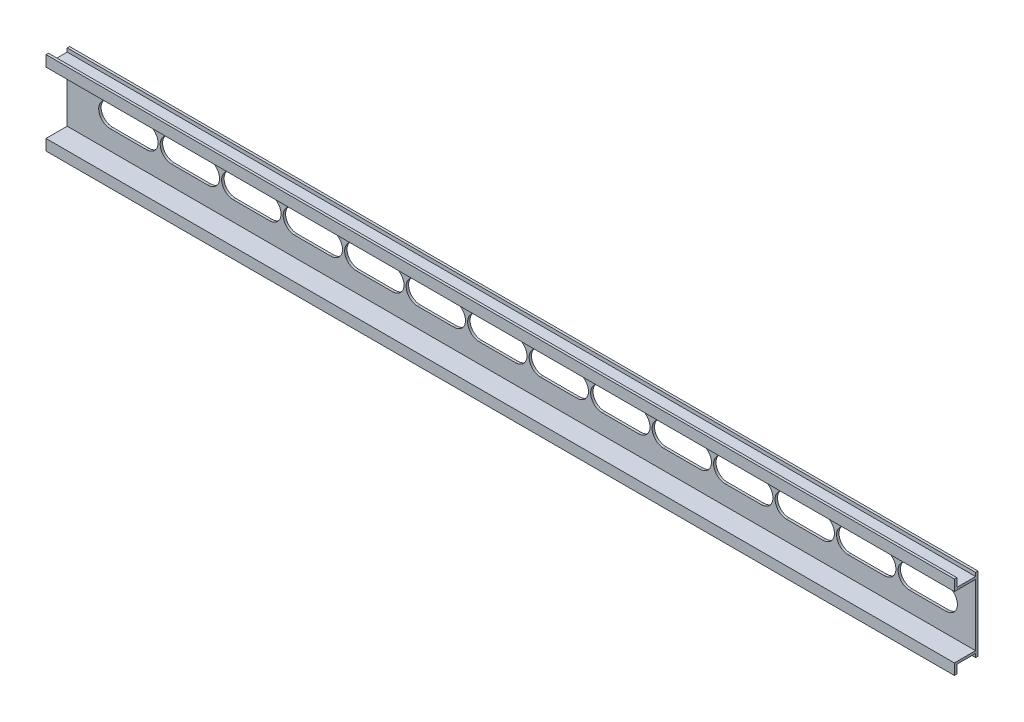
SolidWorks part; units mm, degrees
ref_plane "Front Plane" through (0, 0, 0) normal (0, 0, 1) x (1, 0, 0)
ref_plane "Top Plane" through (0, 0, 0) normal (0, 1, 0) x (1, 0, 0)
ref_plane "Right Plane" through (0, 0, 0) normal (1, 0, 0) x (0, 0, -1)
sketch "Sketch1" plane through (0, 0, 0) normal (1, 0, 0) x (0, 0, -1)
  line L0 (0, 0) -> (96.2341, 0) construction
  line L1 (0, 12.954) -> (0, -12.954)
  line L2 (0, -12.954) -> (-8.89, -12.954)
  line L3 (-8.89, -12.954) -> (-8.89, -17.526)
  line L4 (-8.89, -17.526) -> (-7.874, -17.526)
  line L5 (-7.874, -17.526) -> (-7.874, -13.97)
  line L6 (-7.874, -13.97) -> (0, -13.97)
  line L7 (0, -13.97) -> (0, -15.494)
  line L8 (0, -15.494) -> (1.016, -15.494)
  line L9 (1.016, -15.494) -> (1.016, 15.494)
  line L10 (-7.874, 17.526) -> (-7.874, 13.97)
  line L11 (-8.89, 17.526) -> (-7.874, 17.526)
  line L12 (-8.89, 12.954) -> (-8.89, 17.526)
  line L13 (0, 12.954) -> (-8.89, 12.954)
  line L14 (-7.874, 13.97) -> (0, 13.97)
  line L15 (0, 15.494) -> (1.016, 15.494)
  line L16 (0, 13.97) -> (0, 15.494)
  point P20 (1.016, 0)
  dimension "D1" = 96.2341
  dimension "D2" = 25.908
  dimension "D3" = 9.906
  dimension "D4" = 1.016
  dimension "D5" = 1.016
  dimension "D6" = 1.016
  dimension "D7" = 30.988
  dimension "D8" = 1.016
  dimension "D9" = 35.052
extrude "Boss-Extrude1" add sketch "Sketch1" along normal blind 381
sketch "Sketch2" plane through (0, 0, -1.016) normal (0, 0, -1) x (-1, 0, 0)
  line L0 (-368.554, 0) -> (-353.314, 0) construction
  line L1 (-368.554, 4.826) -> (-353.314, 4.826)
  line L2 (-368.554, -4.826) -> (-353.314, -4.826)
  line L3 (-381, -15.494) -> (-381, 15.494) construction
  line L4 (-342.7632, 0) -> (-327.5232, 0) construction
  line L5 (-342.7632, 4.826) -> (-327.5232, 4.826)
  line L6 (-342.7632, -4.826) -> (-327.5232, -4.826)
  line L7 (-316.9725, 0) -> (-301.7325, 0) construction
  line L8 (-316.9725, 4.826) -> (-301.7325, 4.826)
  line L9 (-316.9725, -4.826) -> (-301.7325, -4.826)
  line L10 (-291.1817, 0) -> (-275.9417, 0) construction
  line L11 (-291.1817, 4.826) -> (-275.9417, 4.826)
  line L12 (-291.1817, -4.826) -> (-275.9417, -4.826)
  line L13 (-265.3909, 0) -> (-250.1509, 0) construction
  line L14 (-265.3909, 4.826) -> (-250.1509, 4.826)
  line L15 (-265.3909, -4.826) -> (-250.1509, -4.826)
  line L16 (-239.6002, 0) -> (-224.3602, 0) construction
  line L17 (-239.6002, 4.826) -> (-224.3602, 4.826)
  line L18 (-239.6002, -4.826) -> (-224.3602, -4.826)
  line L19 (-213.8094, 0) -> (-198.5694, 0) construction
  line L20 (-213.8094, 4.826) -> (-198.5694, 4.826)
  line L21 (-213.8094, -4.826) -> (-198.5694, -4.826)
  line L22 (-188.0186, 0) -> (-172.7786, 0) construction
  line L23 (-188.0186, 4.826) -> (-172.7786, 4.826)
  line L24 (-188.0186, -4.826) -> (-172.7786, -4.826)
  line L25 (-162.2278, 0) -> (-146.9878, 0) construction
  line L26 (-162.2278, 4.826) -> (-146.9878, 4.826)
  line L27 (-162.2278, -4.826) -> (-146.9878, -4.826)
  line L28 (-136.4371, 0) -> (-121.1971, 0) construction
  line L29 (-136.4371, 4.826) -> (-121.1971, 4.826)
  line L30 (-136.4371, -4.826) -> (-121.1971, -4.826)
  line L31 (-110.6463, 0) -> (-95.4063, 0) construction
  line L32 (-110.6463, 4.826) -> (-95.4063, 4.826)
  line L33 (-110.6463, -4.826) -> (-95.4063, -4.826)
  line L34 (-84.8555, 0) -> (-69.6155, 0) construction
  line L35 (-84.8555, 4.826) -> (-69.6155, 4.826)
  line L36 (-84.8555, -4.826) -> (-69.6155, -4.826)
  line L37 (-59.0648, 0) -> (-43.8248, 0) construction
  line L38 (-59.0648, 4.826) -> (-43.8248, 4.826)
  line L39 (-59.0648, -4.826) -> (-43.8248, -4.826)
  line L40 (-33.274, 0) -> (-18.034, 0) construction
  line L41 (-33.274, 4.826) -> (-18.034, 4.826)
  line L42 (-33.274, -4.826) -> (-18.034, -4.826)
  line L43 (0, -15.494) -> (0, 15.494) construction
  arc A0 (-368.554, 4.826) -> (-368.554, -4.826) centre (-368.554, 0) ccw
  arc A1 (-353.314, -4.826) -> (-353.314, 4.826) centre (-353.314, 0) ccw
  arc A2 (-342.7632, 4.826) -> (-342.7632, -4.826) centre (-342.7632, 0) ccw
  arc A3 (-327.5232, -4.826) -> (-327.5232, 4.826) centre (-327.5232, 0) ccw
  arc A4 (-316.9725, 4.826) -> (-316.9725, -4.826) centre (-316.9725, 0) ccw
  arc A5 (-301.7325, -4.826) -> (-301.7325, 4.826) centre (-301.7325, 0) ccw
  arc A6 (-291.1817, 4.826) -> (-291.1817, -4.826) centre (-291.1817, 0) ccw
  arc A7 (-275.9417, -4.826) -> (-275.9417, 4.826) centre (-275.9417, 0) ccw
  arc A8 (-265.3909, 4.826) -> (-265.3909, -4.826) centre (-265.3909, 0) ccw
  arc A9 (-250.1509, -4.826) -> (-250.1509, 4.826) centre (-250.1509, 0) ccw
  arc A10 (-239.6002, 4.826) -> (-239.6002, -4.826) centre (-239.6002, 0) ccw
  arc A11 (-224.3602, -4.826) -> (-224.3602, 4.826) centre (-224.3602, 0) ccw
  arc A12 (-213.8094, 4.826) -> (-213.8094, -4.826) centre (-213.8094, 0) ccw
  arc A13 (-198.5694, -4.826) -> (-198.5694, 4.826) centre (-198.5694, 0) ccw
  arc A14 (-188.0186, 4.826) -> (-188.0186, -4.826) centre (-188.0186, 0) ccw
  arc A15 (-172.7786, -4.826) -> (-172.7786, 4.826) centre (-172.7786, 0) ccw
  arc A16 (-162.2278, 4.826) -> (-162.2278, -4.826) centre (-162.2278, 0) ccw
  arc A17 (-146.9878, -4.826) -> (-146.9878, 4.826) centre (-146.9878, 0) ccw
  arc A18 (-136.4371, 4.826) -> (-136.4371, -4.826) centre (-136.4371, 0) ccw
  arc A19 (-121.1971, -4.826) -> (-121.1971, 4.826) centre (-121.1971, 0) ccw
  arc A20 (-110.6463, 4.826) -> (-110.6463, -4.826) centre (-110.6463, 0) ccw
  arc A21 (-95.4063, -4.826) -> (-95.4063, 4.826) centre (-95.4063, 0) ccw
  arc A22 (-84.8555, 4.826) -> (-84.8555, -4.826) centre (-84.8555, 0) ccw
  arc A23 (-69.6155, -4.826) -> (-69.6155, 4.826) centre (-69.6155, 0) ccw
  arc A24 (-59.0648, 4.826) -> (-59.0648, -4.826) centre (-59.0648, 0) ccw
  arc A25 (-43.8248, -4.826) -> (-43.8248, 4.826) centre (-43.8248, 0) ccw
  arc A26 (-33.274, 4.826) -> (-33.274, -4.826) centre (-33.274, 0) ccw
  arc A27 (-18.034, -4.826) -> (-18.034, 4.826) centre (-18.034, 0) ccw
  point P3 (-360.934, 0)
  point P8 (-373.38, 0)
  point P9 (-348.488, 0)
  point P15 (-335.1432, 0)
  point P22 (-309.3525, 0)
  point P29 (-283.5617, 0)
  point P36 (-257.7709, 0)
  point P43 (-231.9802, 0)
  point P50 (-206.1894, 0)
  point P57 (-180.3986, 0)
  point P64 (-154.6078, 0)
  point P71 (-128.8171, 0)
  point P78 (-103.0263, 0)
  point P85 (-77.2355, 0)
  point P92 (-51.4448, 0)
  point P99 (-25.654, 0)
  dimension "D1" = 4.826
  dimension "D2" = 24.892
  dimension "D3" = 20.066
  dimension "D5" = 18.034
  dimension "D4" = 14
extrude "Cut-Extrude1" cut sketch "Sketch2" against normal through all
